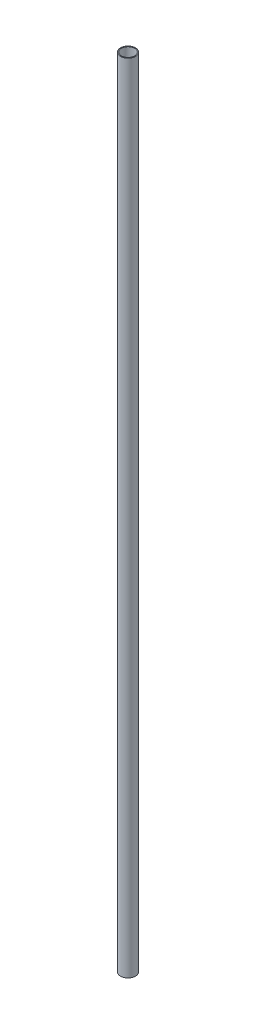
SolidWorks part; units mm, degrees
ref_plane "Front Plane" through (0, 0, 0) normal (0, 0, 1) x (1, 0, 0)
ref_plane "Top Plane" through (0, 0, 0) normal (0, 1, 0) x (1, 0, 0)
ref_plane "Right Plane" through (0, 0, 0) normal (1, 0, 0) x (0, 0, -1)
sketch "Sketch1" plane through (0, 0, 0) normal (0, 1, 0) x (1, 0, 0)
  circle A0 centre (0, 0) radius 3.81
  circle A1 centre (0, 0) radius 3.3655
extrude "Boss-Extrude1" add sketch "Sketch1" along normal blind 406.4
